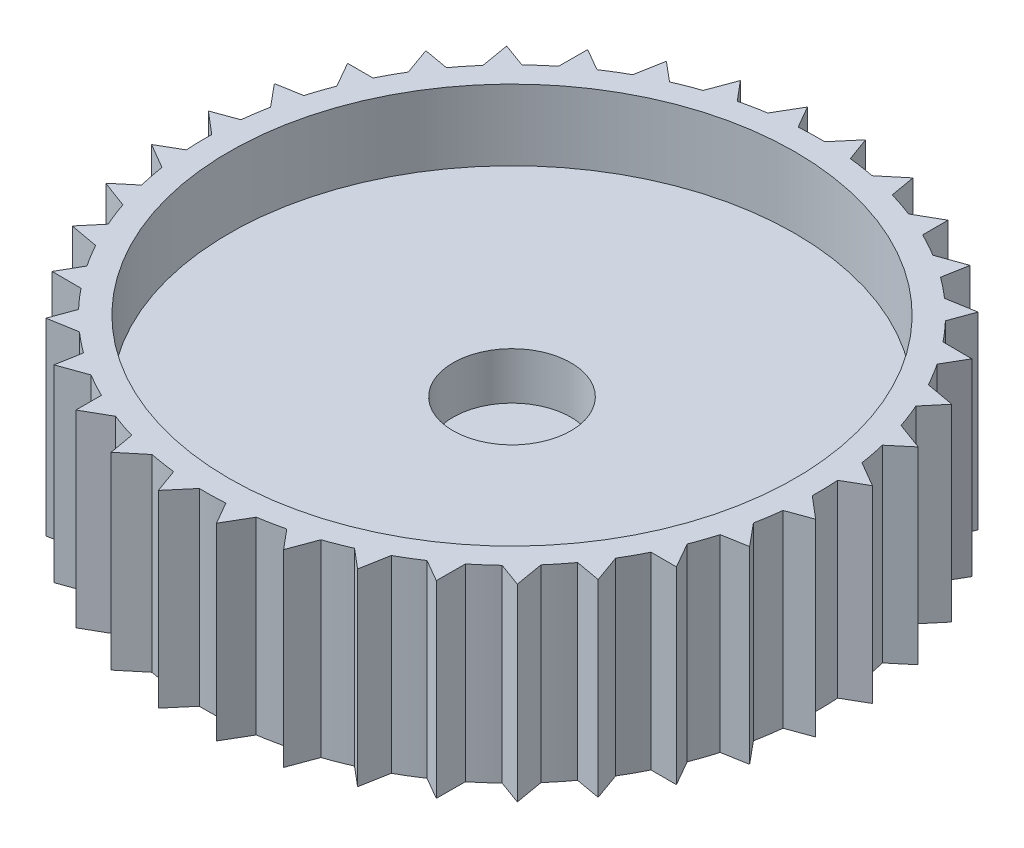
SolidWorks part; units mm, degrees
ref_plane "Front Plane" through (0, 0, 0) normal (0, 0, 1) x (1, 0, 0)
ref_plane "Top Plane" through (0, 0, 0) normal (0, 1, 0) x (1, 0, 0)
ref_plane "Right Plane" through (0, 0, 0) normal (1, 0, 0) x (0, 0, -1)
other "Configuration Table"
sketch "草图1" plane through (0, 0, 0) normal (0, 1, 0) x (1, 0, 0)
  circle A0 centre (0, 0) radius 13
  dimension "D1" = 26
extrude "凸台-拉伸1" add sketch "草图1" along normal blind 8
sketch "草图2" plane through (0, 8, 0) normal (0, 1, 0) x (1, 0, 0)
  circle A0 centre (0, 0) radius 12
  dimension "D1" = 24
extrude "切除-拉伸1" cut sketch "草图2" against normal blind 3
sketch "草图3" plane through (0, 8, 0) normal (0, 1, 0) x (1, 0, 0)
  line L0 (-12.1237, 4.6922) -> (-11.0446, 4.6922)
  line L1 (-12.1237, 4.6922) -> (-12.7329, 5.7609)
  line L2 (-11.0446, 4.6922) -> (-11.6538, 5.7609)
  line L3 (-12.7329, 5.7609) -> (-11.6538, 5.7609)
  line L4 (-11.1247, 6.7262) -> (-10.062, 6.5388)
  line L5 (-11.1247, 6.7262) -> (-11.5391, 7.8844)
  line L6 (-11.5391, 7.8844) -> (-10.4764, 7.6971)
  line L7 (-10.062, 6.5388) -> (-10.4764, 7.6971)
  line L8 (-9.7877, 8.5558) -> (-8.7737, 8.1867)
  line L9 (-9.7877, 8.5558) -> (-9.9947, 9.7684)
  line L10 (-9.9947, 9.7684) -> (-8.9807, 9.3993)
  line L11 (-8.7737, 8.1867) -> (-8.9807, 9.3993)
  line L12 (-8.1533, 10.1254) -> (-7.2188, 9.5859)
  line L13 (-8.1533, 10.1254) -> (-8.1465, 11.3556)
  line L14 (-8.1465, 11.3556) -> (-7.2121, 10.816)
  line L15 (-7.2188, 9.5859) -> (-7.2121, 10.816)
  line L16 (-6.2712, 11.3874) -> (-5.4446, 10.6938)
  line L17 (-6.2712, 11.3874) -> (-6.0509, 12.5977)
  line L18 (-6.0509, 12.5977) -> (-5.2243, 11.9041)
  line L19 (-5.4446, 10.6938) -> (-5.2243, 11.9041)
  line L20 (-4.1985, 12.3034) -> (-3.5049, 11.4767)
  line L21 (-4.1985, 12.3034) -> (-3.7714, 13.457)
  line L22 (-3.7714, 13.457) -> (-3.0778, 12.6304)
  line L23 (-3.5049, 11.4767) -> (-3.0778, 12.6304)
  line L24 (-1.9983, 12.8455) -> (-1.4587, 11.911)
  line L25 (-1.9983, 12.8455) -> (-1.3773, 13.9075)
  line L26 (-1.3773, 13.9075) -> (-0.8378, 12.973)
  line L27 (-1.4587, 11.911) -> (-0.8378, 12.973)
  line L28 (0.2627, 12.9973) -> (0.6317, 11.9834)
  line L29 (0.2627, 12.9973) -> (1.0586, 13.9354)
  line L30 (1.0586, 13.9354) -> (1.4277, 12.9214)
  line L31 (0.6317, 11.9834) -> (1.4277, 12.9214)
  line L32 (2.5157, 12.7543) -> (2.703, 11.6916)
  line L33 (2.5157, 12.7543) -> (3.4624, 13.5398)
  line L34 (3.4624, 13.5398) -> (3.6497, 12.4772)
  line L35 (2.703, 11.6916) -> (3.6497, 12.4772)
  line L36 (4.6922, 12.1237) -> (4.6922, 11.0446)
  line L37 (4.6922, 12.1237) -> (5.7609, 12.7329)
  line L38 (5.7609, 12.7329) -> (5.7609, 11.6538)
  line L39 (4.6922, 11.0446) -> (5.7609, 11.6538)
  line L40 (6.7262, 11.1247) -> (6.5388, 10.062)
  line L41 (6.7262, 11.1247) -> (7.8844, 11.5391)
  line L42 (7.8844, 11.5391) -> (7.6971, 10.4764)
  line L43 (6.5388, 10.062) -> (7.6971, 10.4764)
  line L44 (8.5558, 9.7877) -> (8.1867, 8.7737)
  line L45 (8.5558, 9.7877) -> (9.7684, 9.9947)
  line L46 (9.7684, 9.9947) -> (9.3993, 8.9807)
  line L47 (8.1867, 8.7737) -> (9.3993, 8.9807)
  line L48 (10.1254, 8.1533) -> (9.5859, 7.2188)
  line L49 (10.1254, 8.1533) -> (11.3556, 8.1465)
  line L50 (11.3556, 8.1465) -> (10.816, 7.2121)
  line L51 (9.5859, 7.2188) -> (10.816, 7.2121)
  line L52 (11.3874, 6.2712) -> (10.6938, 5.4446)
  line L53 (11.3874, 6.2712) -> (12.5977, 6.0509)
  line L54 (12.5977, 6.0509) -> (11.9041, 5.2243)
  line L55 (10.6938, 5.4446) -> (11.9041, 5.2243)
  line L56 (12.3034, 4.1985) -> (11.4767, 3.5049)
  line L57 (12.3034, 4.1985) -> (13.457, 3.7714)
  line L58 (13.457, 3.7714) -> (12.6304, 3.0778)
  line L59 (11.4767, 3.5049) -> (12.6304, 3.0778)
  line L60 (12.8455, 1.9983) -> (11.911, 1.4587)
  line L61 (12.8455, 1.9983) -> (13.9075, 1.3773)
  line L62 (13.9075, 1.3773) -> (12.973, 0.8378)
  line L63 (11.911, 1.4587) -> (12.973, 0.8378)
  line L64 (12.9973, -0.2627) -> (11.9834, -0.6317)
  line L65 (12.9973, -0.2627) -> (13.9354, -1.0586)
  line L66 (13.9354, -1.0586) -> (12.9214, -1.4277)
  line L67 (11.9834, -0.6317) -> (12.9214, -1.4277)
  line L68 (12.7543, -2.5157) -> (11.6916, -2.703)
  line L69 (12.7543, -2.5157) -> (13.5398, -3.4624)
  line L70 (13.5398, -3.4624) -> (12.4772, -3.6497)
  line L71 (11.6916, -2.703) -> (12.4772, -3.6497)
  line L72 (12.1237, -4.6922) -> (11.0446, -4.6922)
  line L73 (12.1237, -4.6922) -> (12.7329, -5.7609)
  line L74 (12.7329, -5.7609) -> (11.6538, -5.7609)
  line L75 (11.0446, -4.6922) -> (11.6538, -5.7609)
  line L76 (11.1247, -6.7262) -> (10.062, -6.5388)
  line L77 (11.1247, -6.7262) -> (11.5391, -7.8844)
  line L78 (11.5391, -7.8844) -> (10.4764, -7.6971)
  line L79 (10.062, -6.5388) -> (10.4764, -7.6971)
  line L80 (9.7877, -8.5558) -> (8.7737, -8.1867)
  line L81 (9.7877, -8.5558) -> (9.9947, -9.7684)
  line L82 (9.9947, -9.7684) -> (8.9807, -9.3993)
  line L83 (8.7737, -8.1867) -> (8.9807, -9.3993)
  line L84 (8.1533, -10.1254) -> (7.2188, -9.5859)
  line L85 (8.1533, -10.1254) -> (8.1465, -11.3556)
  line L86 (8.1465, -11.3556) -> (7.2121, -10.816)
  line L87 (7.2188, -9.5859) -> (7.2121, -10.816)
  line L88 (6.2712, -11.3874) -> (5.4446, -10.6938)
  line L89 (6.2712, -11.3874) -> (6.0509, -12.5977)
  line L90 (6.0509, -12.5977) -> (5.2243, -11.9041)
  line L91 (5.4446, -10.6938) -> (5.2243, -11.9041)
  line L92 (4.1985, -12.3034) -> (3.5049, -11.4767)
  line L93 (4.1985, -12.3034) -> (3.7714, -13.457)
  line L94 (3.7714, -13.457) -> (3.0778, -12.6304)
  line L95 (3.5049, -11.4767) -> (3.0778, -12.6304)
  line L96 (1.9983, -12.8455) -> (1.4587, -11.911)
  line L97 (1.9983, -12.8455) -> (1.3773, -13.9075)
  line L98 (1.3773, -13.9075) -> (0.8378, -12.973)
  line L99 (1.4587, -11.911) -> (0.8378, -12.973)
  line L100 (-0.2627, -12.9973) -> (-0.6317, -11.9834)
  line L101 (-0.2627, -12.9973) -> (-1.0586, -13.9354)
  line L102 (-1.0586, -13.9354) -> (-1.4277, -12.9214)
  line L103 (-0.6317, -11.9834) -> (-1.4277, -12.9214)
  line L104 (-2.5157, -12.7543) -> (-2.703, -11.6916)
  line L105 (-2.5157, -12.7543) -> (-3.4624, -13.5398)
  line L106 (-3.4624, -13.5398) -> (-3.6497, -12.4772)
  line L107 (-2.703, -11.6916) -> (-3.6497, -12.4772)
  line L108 (-4.6922, -12.1237) -> (-4.6922, -11.0446)
  line L109 (-4.6922, -12.1237) -> (-5.7609, -12.7329)
  line L110 (-5.7609, -12.7329) -> (-5.7609, -11.6538)
  line L111 (-4.6922, -11.0446) -> (-5.7609, -11.6538)
  line L112 (-6.7262, -11.1247) -> (-6.5388, -10.062)
  line L113 (-6.7262, -11.1247) -> (-7.8844, -11.5391)
  line L114 (-7.8844, -11.5391) -> (-7.6971, -10.4764)
  line L115 (-6.5388, -10.062) -> (-7.6971, -10.4764)
  line L116 (-8.5558, -9.7877) -> (-8.1867, -8.7737)
  line L117 (-8.5558, -9.7877) -> (-9.7684, -9.9947)
  line L118 (-9.7684, -9.9947) -> (-9.3993, -8.9807)
  line L119 (-8.1867, -8.7737) -> (-9.3993, -8.9807)
  line L120 (-10.1254, -8.1533) -> (-9.5859, -7.2188)
  line L121 (-10.1254, -8.1533) -> (-11.3556, -8.1465)
  line L122 (-11.3556, -8.1465) -> (-10.816, -7.2121)
  line L123 (-9.5859, -7.2188) -> (-10.816, -7.2121)
  line L124 (-11.3874, -6.2712) -> (-10.6938, -5.4446)
  line L125 (-11.3874, -6.2712) -> (-12.5977, -6.0509)
  line L126 (-12.5977, -6.0509) -> (-11.9041, -5.2243)
  line L127 (-10.6938, -5.4446) -> (-11.9041, -5.2243)
  line L128 (-12.3034, -4.1985) -> (-11.4767, -3.5049)
  line L129 (-12.3034, -4.1985) -> (-13.457, -3.7714)
  line L130 (-13.457, -3.7714) -> (-12.6304, -3.0778)
  line L131 (-11.4767, -3.5049) -> (-12.6304, -3.0778)
  line L132 (-12.8455, -1.9983) -> (-11.911, -1.4587)
  line L133 (-12.8455, -1.9983) -> (-13.9075, -1.3773)
  line L134 (-13.9075, -1.3773) -> (-12.973, -0.8378)
  line L135 (-11.911, -1.4587) -> (-12.973, -0.8378)
  line L136 (-12.9973, 0.2627) -> (-11.9834, 0.6317)
  line L137 (-12.9973, 0.2627) -> (-13.9354, 1.0586)
  line L138 (-13.9354, 1.0586) -> (-12.9214, 1.4277)
  line L139 (-11.9834, 0.6317) -> (-12.9214, 1.4277)
  line L140 (-12.7543, 2.5157) -> (-11.6916, 2.703)
  line L141 (-12.7543, 2.5157) -> (-13.5398, 3.4624)
  line L142 (-13.5398, 3.4624) -> (-12.4772, 3.6497)
  line L143 (-11.6916, 2.703) -> (-12.4772, 3.6497)
  line L144 (-11.6538, 5.7609) -> (-12.1237, 4.6922) construction
  circle A0 centre (0, 0) radius 13 construction
  circle A1 centre (0, 0) radius 12 construction
  point P151 (0, 0)
  dimension "D1" = 36
extrude "凸台-拉伸2" add sketch "草图3" against normal through all
sketch "草图4" plane through (0, 5, 0) normal (0, 1, 0) x (1, 0, 0)
  circle A0 centre (0, 0) radius 2.5
  dimension "D1" = 5
extrude "切除-拉伸2" cut sketch "草图4" against normal blind 2
